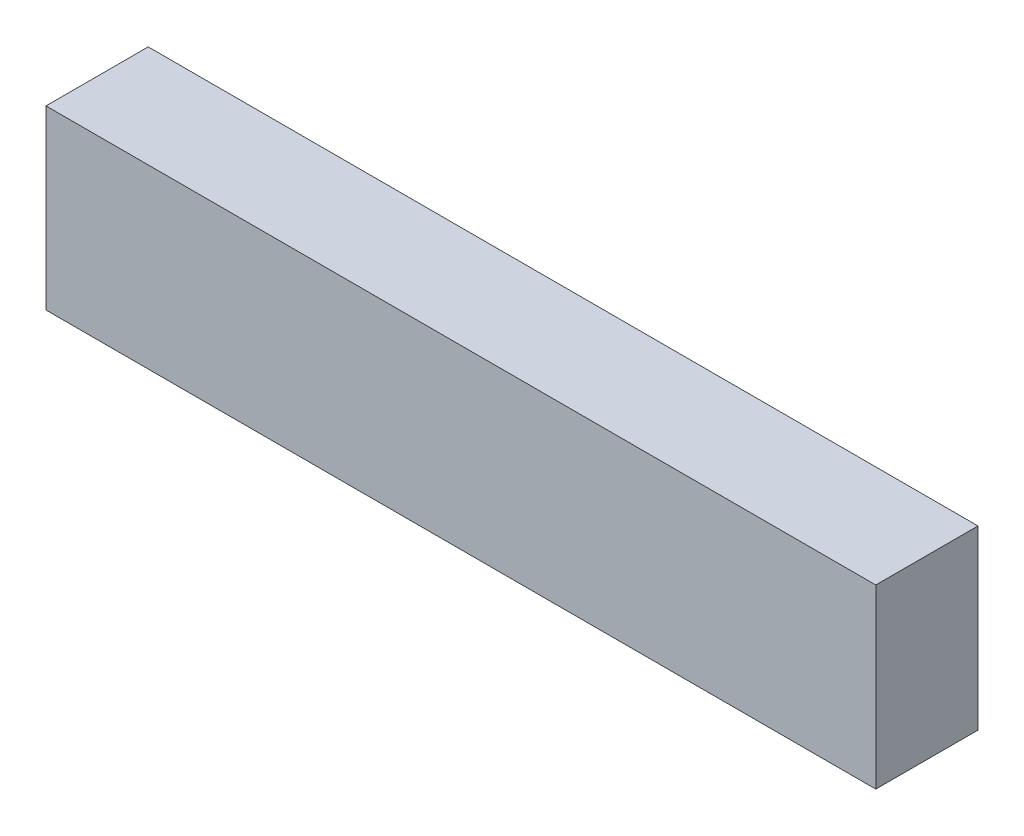
SolidWorks part; units mm, degrees
ref_plane "Front Plane" through (0, 0, 0) normal (0, 0, 1) x (1, 0, 0)
ref_plane "Top Plane" through (0, 0, 0) normal (0, 1, 0) x (1, 0, 0)
ref_plane "Right Plane" through (0, 0, 0) normal (1, 0, 0) x (0, 0, -1)
sketch "Sketch1" plane through (0, 0, 0) normal (0, 0, 1) x (1, 0, 0)
  line L0 (19.9845, 14.45) -> (79.2368, 14.45) construction
  line L1 (20.1845, 14.25) -> (79.0368, 14.25)
  line L2 (20.1845, 14.25) -> (20.1845, 1.71)
  line L3 (20.1845, 1.71) -> (79.0368, 1.71)
  line L4 (79.0368, 14.25) -> (79.0368, 1.71)
  line L5 (79.2368, 1.51) -> (79.2368, 14.45) construction
  line L6 (79.2368, 1.51) -> (19.9845, 1.51) construction
  line L8 (19.9845, 1.51) -> (19.9845, 14.45) construction
  dimension "D1" = 0.2
  dimension "D2" = 0.2
  dimension "D3" = 0.2
  dimension "D4" = 0.2
extrude "Boss-Extrude1" add sketch "Sketch1" along normal blind 7.25
shell "Shell1" thickness 0.5
equation "\"D2@Sketch1\"=\"D1@Sketch1\""
equation "\"D3@Sketch1\"=\"D1@Sketch1\""
equation "\"D4@Sketch1\"=\"D1@Sketch1\""
